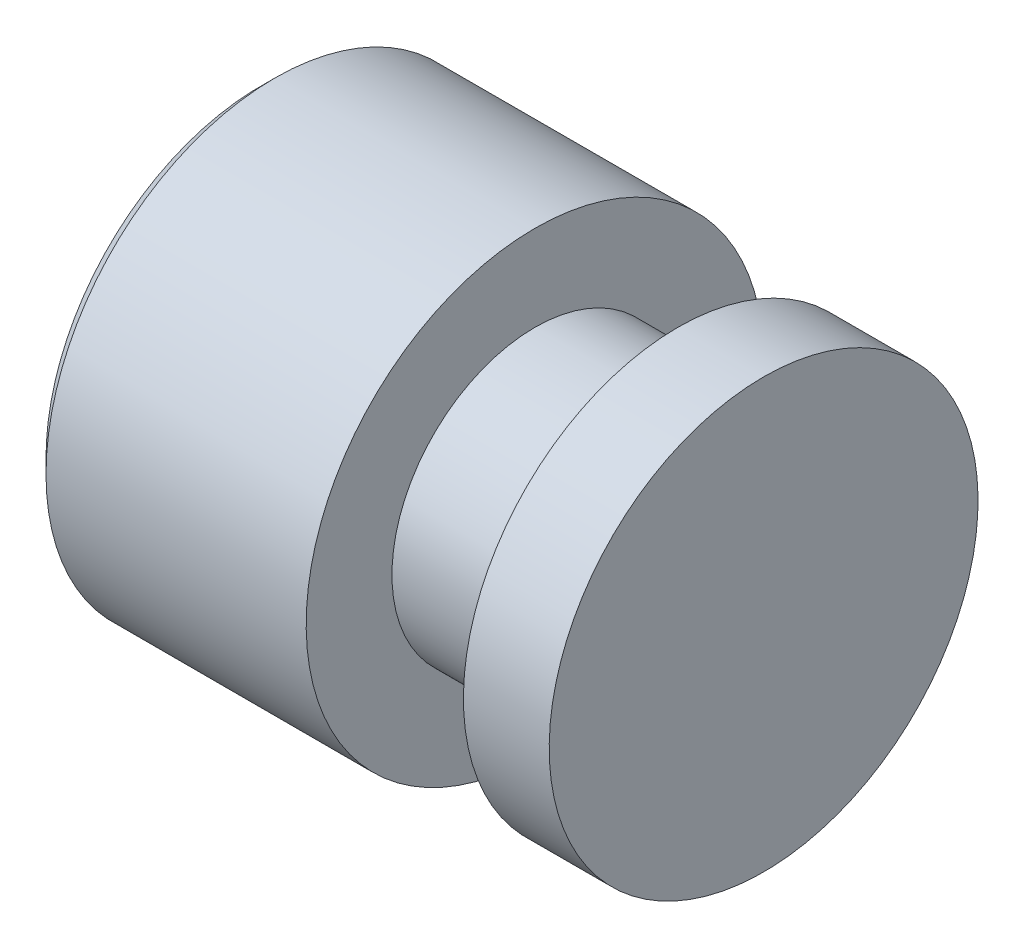
SolidWorks part; units mm, degrees
ref_plane "Front Plane" through (0, 0, 0) normal (0, 0, 1) x (1, 0, 0)
ref_plane "Top Plane" through (0, 0, 0) normal (0, 1, 0) x (1, 0, 0)
ref_plane "Right Plane" through (0, 0, 0) normal (1, 0, 0) x (0, 0, -1)
sketch "Sketch1" plane through (0, 0, 0) normal (0, 0, 1) x (1, 0, 0)
  line L0 (0, 0) -> (0, 8)
  line L1 (0, 8) -> (9.6, 8)
  line L2 (9.6, 8) -> (9.6, 5)
  line L3 (9.6, 5) -> (17.6, 5)
  line L4 (17.6, 5) -> (17.6, 0)
  line L5 (17.6, 0) -> (0, 0)
  dimension "D1" = 8
  dimension "D2" = 9.6
  dimension "D3" = 8
  dimension "D4" = 5
revolve "Revolve1" add sketch "Sketch1" angle 360 about L5
chamfer "Chamfer1" distance 0.5 angle 45 1 edges at (0, 8, 0)
sketch "Sketch2" plane through (17.6, 0, 0) normal (1, 0, 0) x (0, 0, -1)
  circle A0 centre (0, 0) radius 7.5
  circle A1 centre (0, 0) radius 5
  dimension "D1" = 15
extrude "Boss-Extrude1" add sketch "Sketch2" against normal blind 3
